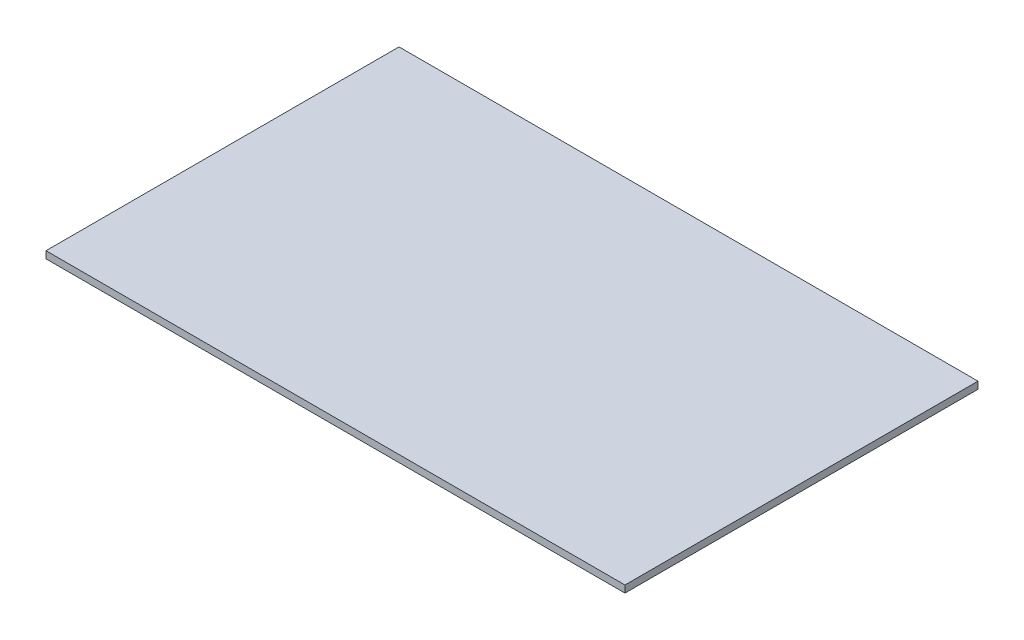
SolidWorks part; units mm, degrees
ref_plane "Plano frontal" through (0, 0, 0) normal (0, 0, 1) x (1, 0, 0)
ref_plane "Plano superior" through (0, 0, 0) normal (0, 1, 0) x (1, 0, 0)
ref_plane "Plano direito" through (0, 0, 0) normal (1, 0, 0) x (0, 0, -1)
sketch "Esboço1" plane through (0, 0, 0) normal (0, 1, 0) x (1, 0, 0)
  line L1 (-41, -25) -> (41, -25)
  line L2 (-41, -25) -> (-41, 25)
  line L3 (-41, 25) -> (41, 25)
  line L4 (41, -25) -> (41, 25)
  line L5 (-41, -25) -> (41, 25) construction
  line L6 (-41, 25) -> (41, -25) construction
  point P0 (0, 0)
  dimension "D1" = 50
  dimension "D2" = 82
extrude "Ressalto-extrusão1" add sketch "Esboço1" along normal blind 1
